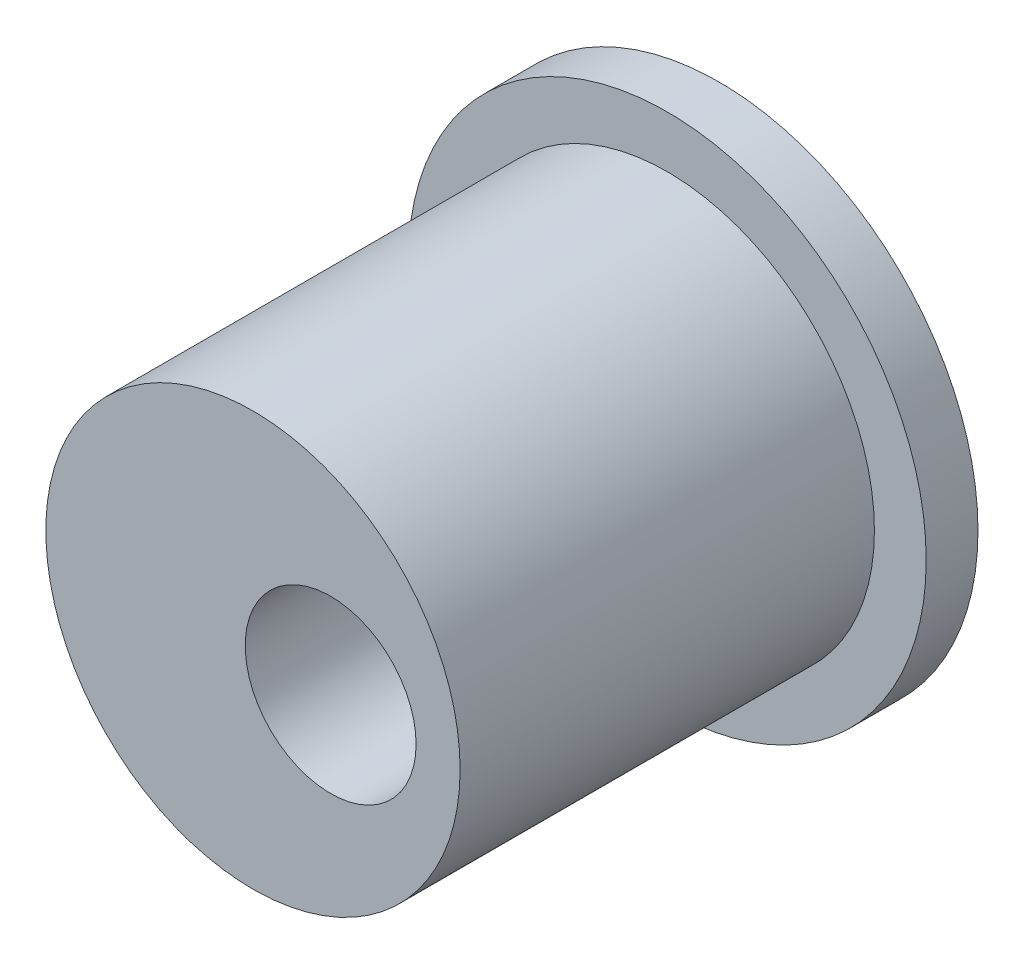
SolidWorks part; units mm, degrees
ref_plane "Front" through (0, 0, 0) normal (0, 0, 1) x (1, 0, 0)
ref_plane "Top" through (0, 0, 0) normal (0, 1, 0) x (1, 0, 0)
ref_plane "Right" through (0, 0, 0) normal (1, 0, 0) x (0, 0, -1)
sketch "Esquisse1" plane through (0, 0, 0) normal (0, 0, 1) x (1, 0, 0)
  circle A0 centre (0, 0) radius 5
  dimension "D1" = 10
extrude "Boss.-Extru.1" add sketch "Esquisse1" along normal blind 1
sketch "Esquisse2" plane through (0, 0, 1) normal (0, 0, 1) x (1, 0, 0)
  circle A0 centre (0, 0) radius 4
  dimension "D1" = 8
extrude "Boss.-Extru.2" add sketch "Esquisse2" along normal blind 8
sketch "Esquisse3" plane through (0, 0, 9) normal (0, 0, 1) x (1, 0, 0)
  line L0 (0, 0) -> (1.5, 0) construction
  circle A0 centre (1.5, 0) radius 1.65
  dimension "D1" = 3.3
  dimension "D2" = 1.5
extrude "Enlèv. mat.-Extru.1" cut sketch "Esquisse3" against normal blind 7
